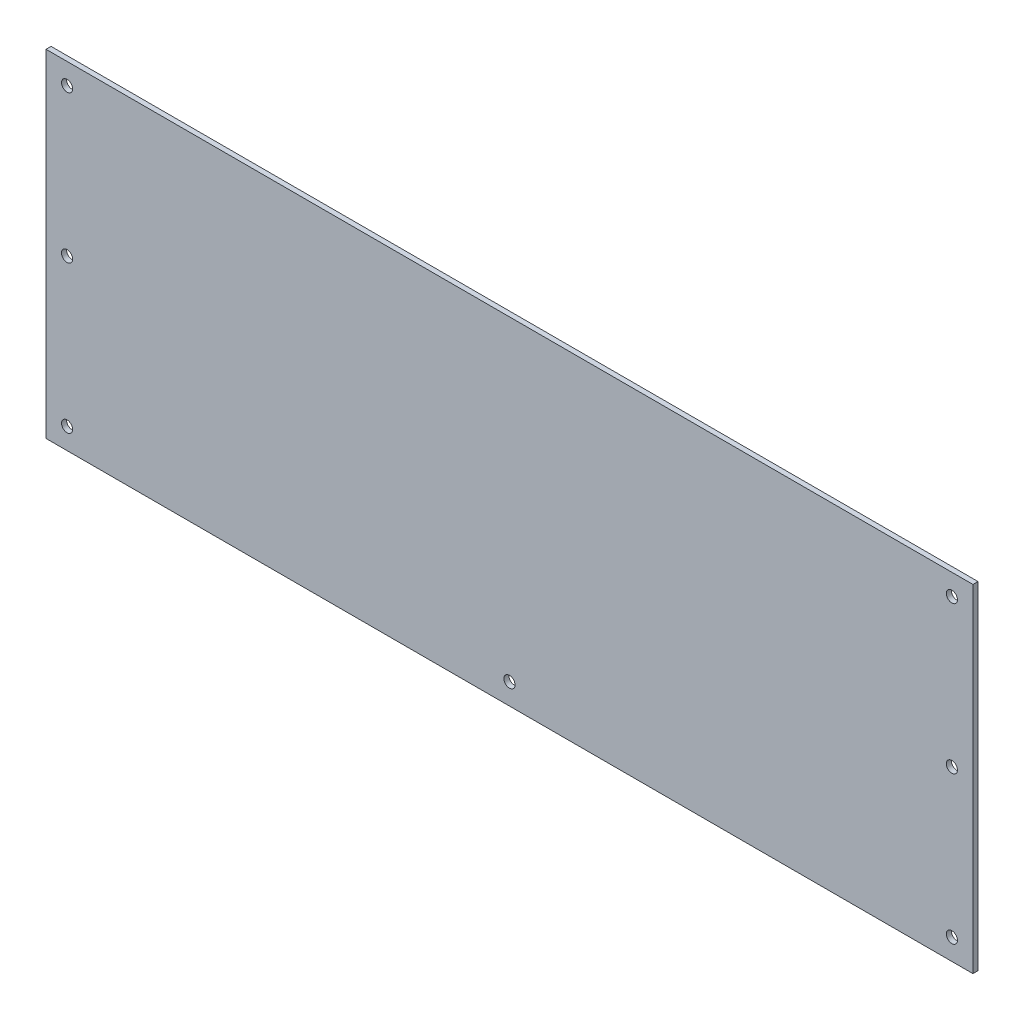
SolidWorks part; units mm, degrees
material "Acrylic (Medium-high impact)"
ref_plane "Front Plane" through (0, 0, 0) normal (0, 0, 1) x (1, 0, 0)
ref_plane "Top Plane" through (0, 0, 0) normal (0, 1, 0) x (1, 0, 0)
ref_plane "Right Plane" through (0, 0, 0) normal (1, 0, 0) x (0, 0, -1)
sketch "Sketch1" plane through (0, 0, 0) normal (0, 0, 1) x (1, 0, 0)
  line L0 (550, 0) -> (550, 150) construction
  line L1 (0, 0) -> (550, 0)
  line L2 (0, 0) -> (0, 200)
  line L3 (0, 200) -> (550, 200)
  line L4 (550, 0) -> (550, 200)
  dimension "D1" = 200
extrude "Boss-Extrude1" add sketch "Sketch1" along normal blind 3
hole_wizard "M6 Clearance Hole1" positions "Sketch2" profile "Sketch3" hole size "M6" standard "ANSI Metric" end condition through all
sketch "Sketch2" plane through (0, 0, 3) normal (0, 0, 1) x (1, 0, 0)
  line L1 (550, 200) -> (0, 200) construction
  line L2 (0, 200) -> (0, 0) construction
  line L3 (0, 0) -> (550, 0) construction
  line L4 (550, 0) -> (550, 200) construction
  point P0 (12.5, 100)
  point P2 (12.5, 187.5)
  point P4 (12.5, 12.5)
  point P6 (275, 12.5)
  point P10 (537.5, 12.5)
  point P12 (537.5, 100)
  point P14 (537.5, 187.5)
  point P40 (0, 100)
  point P42 (275, 0)
  dimension "D1" = 12.5
  dimension "D2" = 12.5
  dimension "D3" = 12.5
  dimension "D4" = 12.5
sketch "Sketch3" plane through (12.5, 100, 3) normal (1, 0, 0) x (0, -1, 0)
  line L0 (0, 0) -> (0, 3)
  line L1 (0, 3) -> (3.3, 3)
  line L2 (3.3, 3) -> (3.3, 0)
  line L5 (3.3, 0) -> (0, 0)
  line L11 (0, -6.35) -> (0, 107.95) construction
  dimension "Thru Hole Dia." = 6.6
  dimension "Thru Hole Depth" = 3
